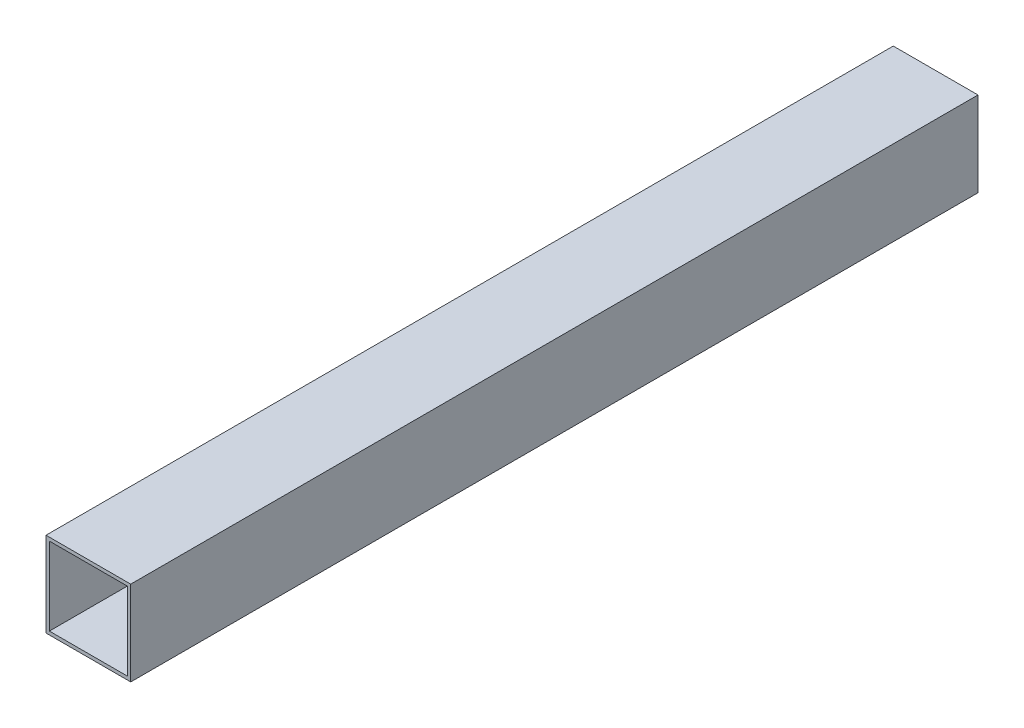
SolidWorks part; units mm, degrees
ref_plane "Alzado" through (0, 0, 0) normal (0, 0, 1) x (1, 0, 0)
ref_plane "Planta" through (0, 0, 0) normal (0, 1, 0) x (1, 0, 0)
ref_plane "Vista lateral" through (0, 0, 0) normal (1, 0, 0) x (0, 0, -1)
sketch "Croquis1" plane through (0, 0, 0) normal (0, 0, 1) x (1, 0, 0)
  line L1 (-107.863, 31.3707) -> (-7.863, 31.3707)
  line L2 (-107.863, 31.3707) -> (-107.863, -68.6293)
  line L3 (-107.863, -68.6293) -> (-7.863, -68.6293)
  line L4 (-7.863, 31.3707) -> (-7.863, -68.6293)
  line L5 (-103.863, 27.3707) -> (-11.863, 27.3707)
  line L6 (-103.863, 27.3707) -> (-103.863, -64.6293)
  line L7 (-103.863, -64.6293) -> (-11.863, -64.6293)
  line L8 (-11.863, 27.3707) -> (-11.863, -64.6293)
  dimension "D1" = 4
  dimension "D2" = 4
  dimension "D3" = 4
  dimension "D4" = 4
  dimension "D5" = 100
  dimension "D6" = 100
extrude "Saliente-Extruir1" add sketch "Croquis1" along normal blind 1000
